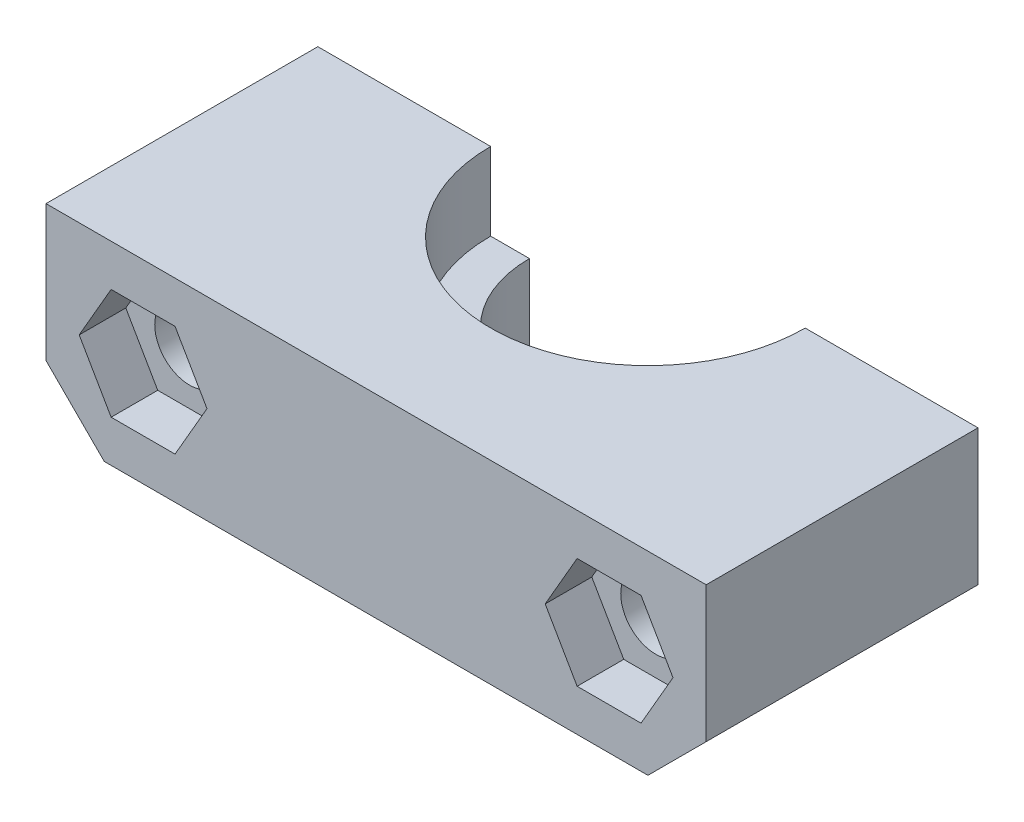
SolidWorks part; units mm, degrees
ref_plane "Front Plane" through (0, 0, 0) normal (0, 0, 1) x (1, 0, 0)
ref_plane "Top Plane" through (0, 0, 0) normal (0, 1, 0) x (1, 0, 0)
ref_plane "Right Plane" through (0, 0, 0) normal (1, 0, 0) x (0, 0, -1)
sketch "Sketch1" plane through (0, 0, 0) normal (0, 1, 0) x (1, 0, 0)
  line L1 (0, 0) -> (34, 0)
  line L2 (0, 0) -> (0, 14)
  line L3 (0, 14) -> (34, 14)
  line L4 (34, 0) -> (34, 14)
  dimension "D1" = 34
  dimension "D2" = 14
extrude "Boss-Extrude1" add sketch "Sketch1" along normal blind 10
sketch "Sketch2" plane through (0, 10, 0) normal (0, 1, 0) x (1, 0, 0)
  line L0 (34, 14) -> (0, 14) construction
  circle A0 centre (17, 14) radius 8.1
  dimension "D1" = 16.2
extrude "Cut-Extrude1" cut sketch "Sketch2" against normal blind 4 contours A0
sketch "Sketch4" plane through (0, 10, 0) normal (0, 1, 0) x (1, 0, 0)
  line L0 (25.1, 14) -> (8.9, 14) construction
  circle A0 centre (17, 14) radius 6.1
  dimension "D1" = 12.2
extrude "Cut-Extrude2" cut sketch "Sketch4" against normal through all both and the other way through all
sketch "Sketch5" plane through (0, 0, -14) normal (0, 0, -1) x (-1, 0, 0)
  line L0 (-29, 5) -> (-34, 5) construction
  line L3 (-34, 10) -> (-34, 0) construction
  line L4 (0, 5) -> (-5, 5) construction
  line L5 (0, 10) -> (0, 0) construction
  circle A0 centre (-29, 5) radius 1.8
  circle A1 centre (-5, 5) radius 1.8
  dimension "D1" = 3.6
  dimension "D2" = 5
extrude "Cut-Extrude3" cut sketch "Sketch5" against normal through all both and the other way through all
sketch "Sketch6" plane through (0, 0, 0) normal (0, 0, 1) x (1, 0, 0)
  line L0 (1.7091, 5) -> (6.6454, 7.85) construction
  line L1 (8.2909, 5) -> (6.6454, 7.85)
  line L2 (6.6454, 7.85) -> (3.3546, 7.85)
  line L3 (3.3546, 7.85) -> (1.7091, 5)
  line L4 (1.7091, 5) -> (3.3546, 2.15)
  line L5 (3.3546, 2.15) -> (6.6454, 2.15)
  line L6 (6.6454, 2.15) -> (8.2909, 5)
  line L7 (25.7091, 5) -> (27.3546, 2.15)
  line L8 (27.3546, 2.15) -> (30.6454, 2.15)
  line L9 (30.6454, 2.15) -> (32.2909, 5)
  line L10 (32.2909, 5) -> (30.6454, 7.85)
  line L11 (30.6454, 7.85) -> (27.3546, 7.85)
  line L12 (27.3546, 7.85) -> (25.7091, 5)
  line L13 (25.7091, 5) -> (30.6454, 7.85) construction
  circle A0 centre (5, 5) radius 2.85 construction
  circle A1 centre (29, 5) radius 2.85 construction
  dimension "D1" = 5.7
extrude "Cut-Extrude4" cut sketch "Sketch6" against normal blind 2.4
chamfer "Chamfer1" distance 3 angle 45 2 edges at (0, 0, -7) (34, 0, -7)
